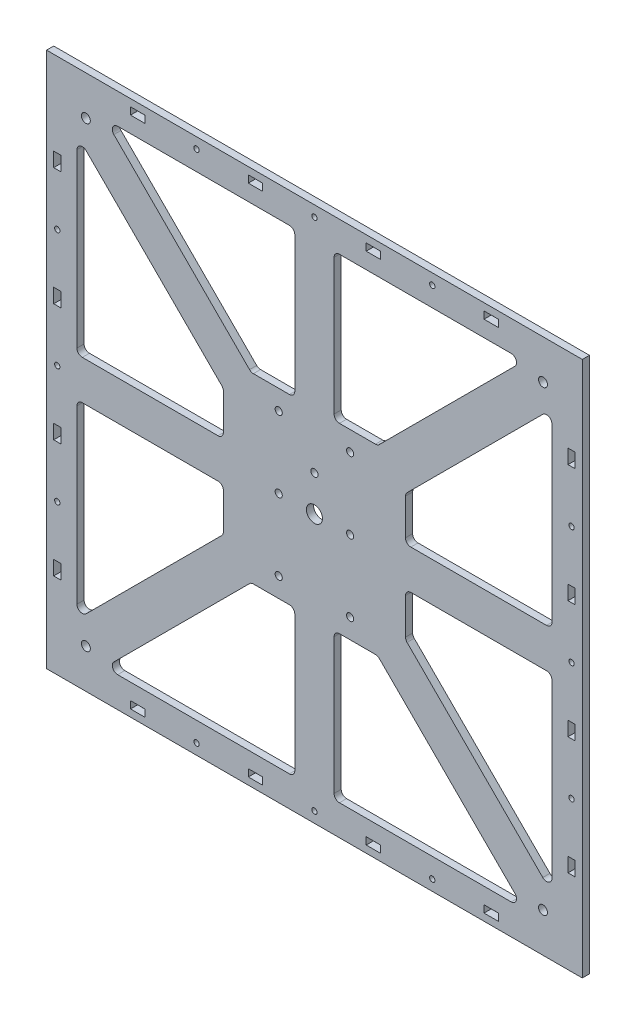
SolidWorks part; units mm, degrees
ref_plane "前视基准面" through (0, 0, 0) normal (0, 0, 1) x (1, 0, 0)
ref_plane "上视基准面" through (0, 0, 0) normal (0, 1, 0) x (1, 0, 0)
ref_plane "右视基准面" through (0, 0, 0) normal (1, 0, 0) x (0, 0, -1)
sketch "草图1" plane through (0, 0, 0) normal (0, 0, 1) x (1, 0, 0)
  line L0 (1.4571, -21.1871) -> (1.4571, -41.1871) construction
  line L1 (1.4571, -41.1871) -> (-18.5429, -41.1871) construction
  line L2 (1.4571, -21.1871) -> (1.4571, 44.8129) construction
  line L4 (151.4571, -41.1871) -> (151.4571, 108.8129)
  line L5 (151.4571, 108.8129) -> (-148.5429, 108.8129)
  line L6 (-148.5429, 108.8129) -> (-148.5429, -191.1871)
  line L7 (-148.5429, -191.1871) -> (151.4571, -191.1871)
  line L8 (151.4571, -191.1871) -> (151.4571, -41.1871)
  line L9 (-148.5429, -41.1871) -> (-161.9412, -41.1871) construction
  line L10 (1.4571, -191.1871) -> (1.4571, -181.0361) construction
  circle A0 centre (1.4571, -21.1871) radius 10 construction
  circle A1 centre (1.4571, -41.1871) radius 4.5
  circle A2 centre (-18.5429, -41.1871) radius 2
  circle A3 centre (-18.5429, -1.1871) radius 2
  circle A4 centre (21.4571, -1.1871) radius 2
  circle A5 centre (21.4571, -41.1871) radius 2
  circle A6 centre (1.4571, -21.1871) radius 241.4173 construction
  circle A7 centre (21.4571, -81.1871) radius 2
  circle A8 centre (-18.5429, -81.1871) radius 2
  dimension "D2" = 300
  dimension "D3" = 300
extrude "凸台-拉伸1" add sketch "草图1" along normal blind 4
sketch "草图2" plane through (0, 0, 4) normal (0, 0, 1) x (1, 0, 0)
  line L0 (-18.5429, -1.1871) -> (21.4571, -41.1871) construction
  circle A0 centre (1.4571, -21.1871) radius 2
extrude "切除-拉伸1" cut sketch "草图2" against normal blind 4 contours A0
sketch "草图3" plane through (0, 0, 4) normal (0, 0, 1) x (1, 0, 0)
  line L1 (96.4421, -183.1721) -> (104.4721, -183.1721)
  line L13 (1.4571, -191.1871) -> (1.4571, -185.1871) construction
  line L14 (-148.5429, -191.1871) -> (151.4571, -191.1871) construction
  line L15 (1.4571, -185.1871) -> (34.4571, -185.1871) construction
  line L16 (34.4571, -185.1871) -> (67.4571, -185.1871) construction
  line L17 (30.4421, -183.1721) -> (38.4721, -183.1721)
  line L18 (30.4421, -183.1721) -> (30.4421, -187.2021)
  line L19 (30.4421, -187.2021) -> (38.4721, -187.2021)
  line L20 (38.4721, -183.1721) -> (38.4721, -187.2021)
  line L21 (30.4421, -183.1721) -> (38.4721, -187.2021) construction
  line L22 (30.4421, -187.2021) -> (38.4721, -183.1721) construction
  line L23 (67.4571, -185.1871) -> (100.4571, -185.1871) construction
  line L24 (96.4421, -183.1721) -> (96.4421, -187.2021)
  line L25 (96.4421, -187.2021) -> (104.4721, -187.2021)
  line L26 (96.4421, -187.2021) -> (104.4721, -183.1721) construction
  line L27 (104.4721, -187.2021) -> (104.4721, -183.1721)
  line L28 (-35.5579, -183.1721) -> (-35.5579, -187.2021)
  line L29 (-27.5279, -183.1721) -> (-35.5579, -183.1721)
  line L30 (-27.5279, -183.1721) -> (-27.5279, -187.2021)
  line L31 (-27.5279, -187.2021) -> (-35.5579, -187.2021)
  line L32 (-93.5279, -183.1721) -> (-93.5279, -187.2021)
  line L33 (-101.5579, -187.2021) -> (-101.5579, -183.1721)
  line L34 (-93.5279, -183.1721) -> (-101.5579, -183.1721)
  line L35 (-93.5279, -187.2021) -> (-101.5579, -187.2021)
  line L36 (-140.5279, 53.7979) -> (-140.5279, 61.8279)
  line L37 (-144.5579, 53.7979) -> (-144.5579, 61.8279)
  line L38 (-144.5579, 61.8279) -> (-140.5279, 61.8279)
  line L39 (-140.5279, 53.7979) -> (-144.5579, 53.7979)
  line L40 (-140.5279, -12.2021) -> (-140.5279, -4.1721)
  line L41 (-140.5279, -4.1721) -> (-144.5579, -4.1721)
  line L42 (-144.5579, -12.2021) -> (-144.5579, -4.1721)
  line L43 (-140.5279, -12.2021) -> (-144.5579, -12.2021)
  line L44 (-140.5279, -70.1721) -> (-144.5579, -70.1721)
  line L45 (-140.5279, -70.1721) -> (-140.5279, -78.2021)
  line L46 (-144.5579, -70.1721) -> (-144.5579, -78.2021)
  line L47 (-140.5279, -78.2021) -> (-144.5579, -78.2021)
  line L48 (-140.5279, -136.1721) -> (-140.5279, -144.2021)
  line L49 (-144.5579, -136.1721) -> (-144.5579, -144.2021)
  line L50 (-140.5279, -136.1721) -> (-144.5579, -136.1721)
  line L51 (-144.5579, -144.2021) -> (-140.5279, -144.2021)
  line L52 (96.4421, 100.7979) -> (104.4721, 100.7979)
  line L53 (96.4421, 104.8279) -> (104.4721, 104.8279)
  line L54 (104.4721, 104.8279) -> (104.4721, 100.7979)
  line L55 (96.4421, 100.7979) -> (96.4421, 104.8279)
  line L56 (30.4421, 100.7979) -> (38.4721, 100.7979)
  line L57 (38.4721, 100.7979) -> (38.4721, 104.8279)
  line L58 (30.4421, 104.8279) -> (38.4721, 104.8279)
  line L59 (30.4421, 100.7979) -> (30.4421, 104.8279)
  line L60 (-27.5279, 100.7979) -> (-27.5279, 104.8279)
  line L61 (-27.5279, 100.7979) -> (-35.5579, 100.7979)
  line L62 (-27.5279, 104.8279) -> (-35.5579, 104.8279)
  line L63 (-35.5579, 100.7979) -> (-35.5579, 104.8279)
  line L64 (-93.5279, 100.7979) -> (-101.5579, 100.7979)
  line L65 (-93.5279, 104.8279) -> (-101.5579, 104.8279)
  line L66 (-93.5279, 100.7979) -> (-93.5279, 104.8279)
  line L67 (-101.5579, 104.8279) -> (-101.5579, 100.7979)
  line L68 (143.4421, -136.1721) -> (143.4421, -144.2021)
  line L69 (147.4721, -136.1721) -> (147.4721, -144.2021)
  line L70 (147.4721, -144.2021) -> (143.4421, -144.2021)
  line L71 (143.4421, -136.1721) -> (147.4721, -136.1721)
  line L72 (143.4421, -70.1721) -> (143.4421, -78.2021)
  line L73 (143.4421, -78.2021) -> (147.4721, -78.2021)
  line L74 (147.4721, -70.1721) -> (147.4721, -78.2021)
  line L75 (143.4421, -70.1721) -> (147.4721, -70.1721)
  line L76 (143.4421, -12.2021) -> (147.4721, -12.2021)
  line L77 (143.4421, -12.2021) -> (143.4421, -4.1721)
  line L78 (147.4721, -12.2021) -> (147.4721, -4.1721)
  line L79 (143.4421, -4.1721) -> (147.4721, -4.1721)
  line L80 (143.4421, 53.7979) -> (143.4421, 61.8279)
  line L81 (147.4721, 53.7979) -> (147.4721, 61.8279)
  line L82 (143.4421, 53.7979) -> (147.4721, 53.7979)
  line L83 (147.4721, 61.8279) -> (143.4421, 61.8279)
  circle A0 centre (1.4571, -185.1871) radius 1.5
  circle A1 centre (67.4571, -185.1871) radius 1.5
  circle A2 centre (-64.5429, -185.1871) radius 1.5
  circle A3 centre (-142.5429, 24.8129) radius 1.5
  circle A4 centre (-142.5429, -41.1871) radius 1.5
  circle A5 centre (-142.5429, -107.1871) radius 1.5
  circle A6 centre (67.4571, 102.8129) radius 1.5
  circle A7 centre (1.4571, 102.8129) radius 1.5
  circle A8 centre (-64.5429, 102.8129) radius 1.5
  circle A9 centre (145.4571, -107.1871) radius 1.5
  circle A10 centre (145.4571, -41.1871) radius 1.5
  circle A11 centre (145.4571, 24.8129) radius 1.5
  dimension "D1" = 8.03
  dimension "D3" = 4
  dimension "D2" = 4.03
extrude "切除-拉伸2" cut sketch "草图3" against normal blind 4
sketch "草图4" plane through (0, 0, 4) normal (0, 0, 1) x (1, 0, 0)
  line L2 (1.4571, 102.8129) -> (-142.5429, 102.8129) construction
  line L3 (-142.5429, 102.8129) -> (-38.5429, -1.1871) construction
  line L4 (1.4571, -1.1871) -> (-38.5429, -1.1871) construction
  line L5 (1.4571, 102.8129) -> (1.4571, -1.1871) construction
  line L6 (-9.5429, 88.8129) -> (-9.5429, 12.8129)
  line L7 (-12.5429, 9.8129) -> (-32.7439, 9.8129)
  line L8 (-110.8652, 86.6915) -> (-34.8652, 10.6915)
  line L9 (-12.5429, 91.8129) -> (-108.7439, 91.8129)
  line L10 (-9.5429, 91.8129) -> (-115.9865, 91.8129) construction
  line L11 (-115.9865, 91.8129) -> (-33.9865, 9.8129) construction
  line L12 (-9.5429, 91.8129) -> (-9.5429, 9.8129) construction
  line L13 (-9.5429, 9.8129) -> (-33.9865, 9.8129) construction
  line L14 (12.4571, 88.8129) -> (12.4571, 12.8129)
  line L15 (15.4571, 9.8129) -> (35.6582, 9.8129)
  line L16 (113.7795, 86.6915) -> (37.7795, 10.6915)
  line L17 (15.4571, 91.8129) -> (111.6582, 91.8129)
  line L18 (1.4571, -41.1871) -> (42.8173, -41.1871) construction
  line L19 (-12.5429, -174.1871) -> (-108.7439, -174.1871)
  line L20 (-110.8652, -169.0658) -> (-34.8652, -93.0658)
  line L21 (-12.5429, -92.1871) -> (-32.7439, -92.1871)
  line L22 (-9.5429, -171.1871) -> (-9.5429, -95.1871)
  line L23 (-49.5429, -27.1871) -> (-49.5429, -6.9861)
  line L24 (15.4571, -174.1871) -> (111.6582, -174.1871)
  line L25 (113.7795, -169.0658) -> (37.7795, -93.0658)
  line L26 (15.4571, -92.1871) -> (35.6582, -92.1871)
  line L27 (12.4571, -171.1871) -> (12.4571, -95.1871)
  line L28 (-128.5429, -30.1871) -> (-52.5429, -30.1871)
  line L29 (-131.5429, -27.1871) -> (-131.5429, 69.0139)
  line L30 (-126.4215, 71.1352) -> (-50.4215, -4.8648)
  line L31 (129.3358, 71.1352) -> (53.3358, -4.8648)
  line L32 (134.4571, -27.1871) -> (134.4571, 69.0139)
  line L33 (131.4571, -30.1871) -> (55.4571, -30.1871)
  line L34 (52.4571, -27.1871) -> (52.4571, -6.9861)
  line L35 (52.4571, -55.1871) -> (52.4571, -75.3882)
  line L36 (131.4571, -52.1871) -> (55.4571, -52.1871)
  line L37 (134.4571, -55.1871) -> (134.4571, -151.3882)
  line L38 (129.3358, -153.5095) -> (53.3358, -77.5095)
  line L39 (-126.4215, -153.5095) -> (-50.4215, -77.5095)
  line L40 (-131.5429, -55.1871) -> (-131.5429, -151.3882)
  line L41 (-128.5429, -52.1871) -> (-52.5429, -52.1871)
  line L42 (-49.5429, -55.1871) -> (-49.5429, -75.3882)
  arc A0 (-108.7439, 91.8129) -> (-110.8652, 86.6915) centre (-108.7439, 88.8129) ccw
  arc A1 (-9.5429, 12.8129) -> (-12.5429, 9.8129) centre (-12.5429, 12.8129) cw
  arc A2 (-32.7439, 9.8129) -> (-34.8652, 10.6915) centre (-32.7439, 12.8129) cw
  arc A3 (-9.5429, 88.8129) -> (-12.5429, 91.8129) centre (-12.5429, 88.8129) ccw
  arc A4 (111.6582, 91.8129) -> (113.7795, 86.6915) centre (111.6582, 88.8129) cw
  arc A5 (12.4571, 88.8129) -> (15.4571, 91.8129) centre (15.4571, 88.8129) cw
  arc A6 (12.4571, 12.8129) -> (15.4571, 9.8129) centre (15.4571, 12.8129) ccw
  arc A7 (35.6582, 9.8129) -> (37.7795, 10.6915) centre (35.6582, 12.8129) ccw
  arc A8 (-9.5429, -171.1871) -> (-12.5429, -174.1871) centre (-12.5429, -171.1871) cw
  arc A9 (-32.7439, -92.1871) -> (-34.8652, -93.0658) centre (-32.7439, -95.1871) ccw
  arc A10 (-9.5429, -95.1871) -> (-12.5429, -92.1871) centre (-12.5429, -95.1871) ccw
  arc A11 (-108.7439, -174.1871) -> (-110.8652, -169.0658) centre (-108.7439, -171.1871) cw
  arc A12 (35.6582, -92.1871) -> (37.7795, -93.0658) centre (35.6582, -95.1871) cw
  arc A13 (12.4571, -95.1871) -> (15.4571, -92.1871) centre (15.4571, -95.1871) cw
  arc A14 (12.4571, -171.1871) -> (15.4571, -174.1871) centre (15.4571, -171.1871) ccw
  arc A15 (111.6582, -174.1871) -> (113.7795, -169.0658) centre (111.6582, -171.1871) ccw
  arc A16 (-128.5429, -30.1871) -> (-131.5429, -27.1871) centre (-128.5429, -27.1871) cw
  arc A17 (-131.5429, 69.0139) -> (-126.4215, 71.1352) centre (-128.5429, 69.0139) cw
  arc A18 (-49.5429, -6.9861) -> (-50.4215, -4.8648) centre (-52.5429, -6.9861) ccw
  arc A19 (-52.5429, -30.1871) -> (-49.5429, -27.1871) centre (-52.5429, -27.1871) ccw
  arc A20 (55.4571, -30.1871) -> (52.4571, -27.1871) centre (55.4571, -27.1871) cw
  arc A21 (52.4571, -6.9861) -> (53.3358, -4.8648) centre (55.4571, -6.9861) cw
  arc A22 (134.4571, 69.0139) -> (129.3358, 71.1352) centre (131.4571, 69.0139) ccw
  arc A23 (131.4571, -30.1871) -> (134.4571, -27.1871) centre (131.4571, -27.1871) ccw
  arc A24 (131.4571, -52.1871) -> (134.4571, -55.1871) centre (131.4571, -55.1871) cw
  arc A25 (134.4571, -151.3882) -> (129.3358, -153.5095) centre (131.4571, -151.3882) cw
  arc A26 (52.4571, -75.3882) -> (53.3358, -77.5095) centre (55.4571, -75.3882) ccw
  arc A27 (55.4571, -52.1871) -> (52.4571, -55.1871) centre (55.4571, -55.1871) ccw
  arc A28 (-52.5429, -52.1871) -> (-49.5429, -55.1871) centre (-52.5429, -55.1871) cw
  arc A29 (-49.5429, -75.3882) -> (-50.4215, -77.5095) centre (-52.5429, -75.3882) cw
  arc A30 (-131.5429, -151.3882) -> (-126.4215, -153.5095) centre (-128.5429, -151.3882) ccw
  arc A31 (-128.5429, -52.1871) -> (-131.5429, -55.1871) centre (-128.5429, -55.1871) ccw
  dimension "D2" = 3
  dimension "D3" = 3
  dimension "D1" = 11
extrude "切除-拉伸3" cut sketch "草图4" against normal blind 4
sketch "草图5" plane through (0, 0, 4) normal (0, 0, 1) x (1, 0, 0)
  line L0 (1.4571, -41.1871) -> (-148.5429, 108.8129) construction
  line L1 (-126.5429, 86.8129) -> (-126.5429, 108.8129) construction
  line L2 (151.4571, 108.8129) -> (-148.5429, 108.8129) construction
  circle A0 centre (-126.5429, 86.8129) radius 2.5
  circle A1 centre (129.4571, 86.8129) radius 2.5
  circle A2 centre (129.4571, -169.1871) radius 2.5
  circle A3 centre (-126.5429, -169.1871) radius 2.5
  dimension "D1" = 4
extrude "切除-拉伸4" cut sketch "草图5" against normal blind 10
